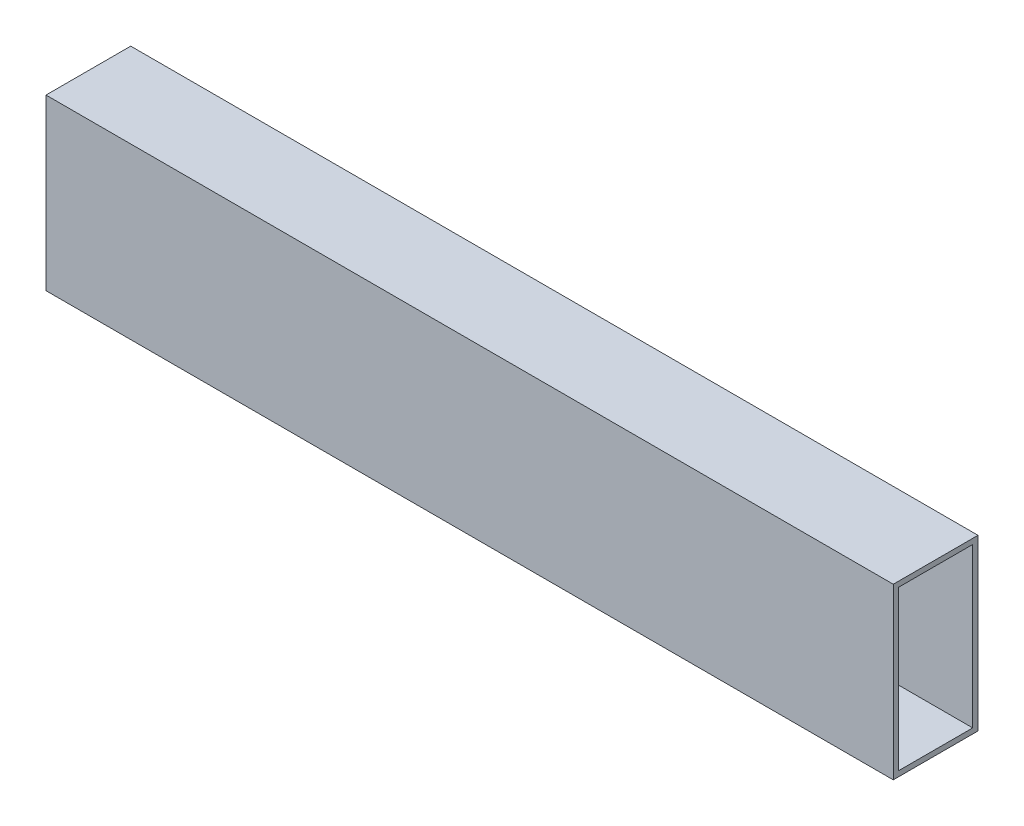
SolidWorks part; units mm, degrees
ref_plane "Front Plane" through (0, 0, 0) normal (0, 0, 1) x (1, 0, 0)
ref_plane "Top Plane" through (0, 0, 0) normal (0, 1, 0) x (1, 0, 0)
ref_plane "Right Plane" through (0, 0, 0) normal (1, 0, 0) x (0, 0, -1)
sketch "Sketch1" plane through (0, 0, 0) normal (1, 0, 0) x (0, 0, -1)
  line L0 (-9.1895, -23.8125) -> (-9.1895, 23.8125)
  line L1 (-10.777, -25.4) -> (14.623, -25.4)
  line L2 (-10.777, -25.4) -> (-10.777, 25.4)
  line L3 (-10.777, 25.4) -> (14.623, 25.4)
  line L4 (14.623, -25.4) -> (14.623, 25.4)
  line L5 (-10.777, -25.4) -> (14.623, 25.4) construction
  line L6 (-10.777, 25.4) -> (14.623, -25.4) construction
  line L11 (-9.1895, 23.8125) -> (13.0355, 23.8125)
  line L12 (13.0355, -23.8125) -> (13.0355, 23.8125)
  line L13 (-9.1895, -23.8125) -> (13.0355, -23.8125)
  dimension "D1" = 50.8
  dimension "D2" = 25.4
  dimension "D3" = 1.5875
extrude "Boss-Extrude1" add sketch "Sketch1" along normal mid plane 254
